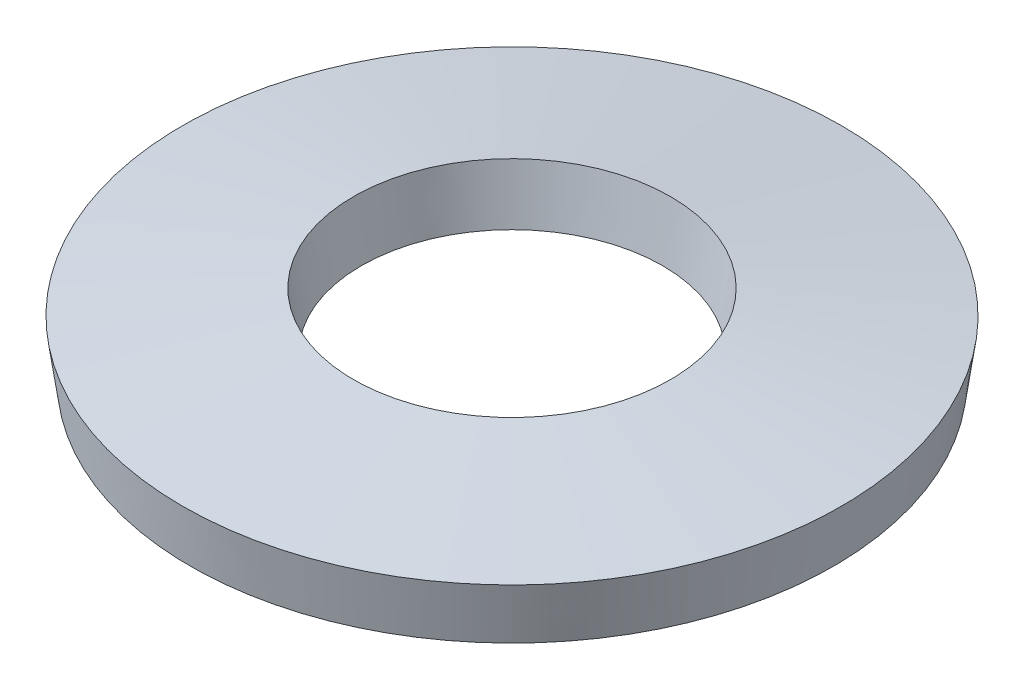
SolidWorks part; units mm, degrees
ref_plane "Front" through (0, 0, 0) normal (0, 0, 1) x (1, 0, 0)
ref_plane "Top" through (0, 0, 0) normal (0, 1, 0) x (1, 0, 0)
ref_plane "Right" through (0, 0, 0) normal (1, 0, 0) x (0, 0, -1)
sketch "Sketch1" plane through (0, 0, 0) normal (0, 0, 1) x (1, 0, 0)
  line L0 (3.4163, 0) -> (1.6, 0.2559)
  line L1 (1.6, 0.2559) -> (1.6837, 0.85)
  line L2 (1.6837, 0.85) -> (3.5, 0.5941)
  line L3 (3.5, 0.5941) -> (3.4163, 0)
  line L4 (0, 0) -> (0, 0.85) construction
  line L5 (-3.5, 0.5941) -> (-3.4163, 0) construction
  line L6 (-1.6837, 0.85) -> (-3.5, 0.5941) construction
  line L7 (-1.6, 0.2559) -> (-1.6837, 0.85) construction
  line L8 (-3.4163, 0) -> (-1.6, 0.2559) construction
  point P5 (1.6418, 0.5529)
  point P8 (-1.6418, 0.5529)
  dimension "ID" = 3.2
  dimension "Thickness" = 0.6
  dimension "D1" = 1.8342
revolve "Revolve1" add sketch "Sketch1" angle 360 about L4
sketch "Sketch15" plane through (0, 0, 0) normal (0, 1, 0) x (1, 0, 0)
  circle A0 centre (0, 0) radius 3.5
  circle A1 centre (0, 0) radius 1.6
ref_plane "Plane10" through (0, 0.85, 0) normal (0, 1, 0) x (-1, 0, 0)
surface "Surface-Knit1"
surface "Surface-Extend1" parameters "D1"=1.27, "D2"=1.27
sketch "Sketch13" plane through (0, 0.85, 0) normal (0, 1, 0) x (-1, 0, 0)
  line L0 (-3.7585, 0.9675) -> (-1.1978, -0.2266)
  line L2 (-3.4163, 0) -> (-1.6, 0) construction
  circle A3 centre (0, 0) radius 1.219
  circle A4 centre (0, 0) radius 1.219 construction
  circle A6 centre (0, 0) radius 3.881
  circle A7 centre (0, 0) radius 3.881 construction
  dimension "D1" = 25
  dimension "D2" = 0.381
  dimension "D3" = 0.381
extrude "Cut-Extrude-Thin12" [suppressed] cut sketch "Sketch13" against normal offset from surface (0.3852 mm away) 0.075 thin
surface "Surface-Knit2"
surface "Surface-Extend2" parameters "D1"=0.762, "D2"=0.762
sketch "Sketch14" plane through (0, 0, 0) normal (0, 1, 0) x (1, 0, 0)
  line L0 (3.7585, -0.9675) -> (1.1978, 0.2266) construction
  line L1 (3.7585, -0.9675) -> (1.1978, 0.2266)
extrude "Cut-Extrude-Thin13" [suppressed] cut sketch "Sketch14" along normal offset from surface (0.0096 mm away) 0.075 thin
chamfer "Chamfer1" [suppressed] distance 0.0675 angle 45
pattern_circular "CirPattern3" [suppressed] count 24 over 360
delete or keep bodies "Body-Delete1" type delete bodies bodies 120
delete or keep bodies "Body-Delete2" type delete bodies bodies 119
equation "\"D1@Cut-Extrude-Thin12\" = \"Thickness@Sketch1\"*.125"
equation "\"D1@Cut-Extrude-Thin13\" = \"D1@Cut-Extrude-Thin12\""
equation "\"D1@Chamfer1\" = \"D1@Cut-Extrude-Thin12\"*.9"
